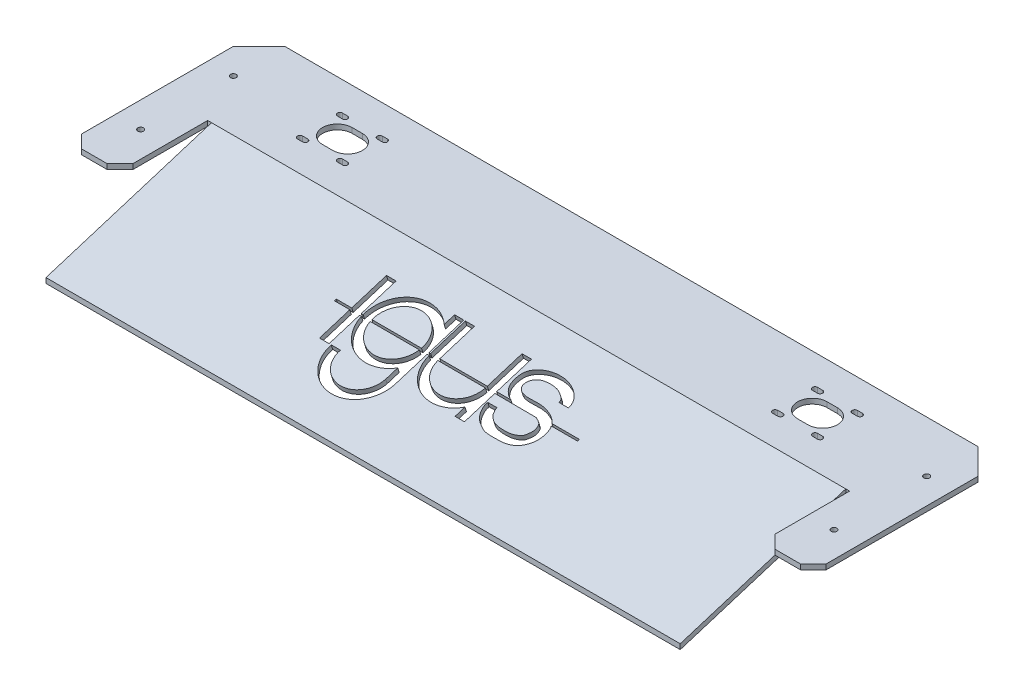
SolidWorks part; units mm, degrees
ref_plane "Front Plane" through (0, 0, 0) normal (0, 0, 1) x (1, 0, 0)
ref_plane "Top Plane" through (0, 0, 0) normal (0, 1, 0) x (1, 0, 0)
ref_plane "Right Plane" through (0, 0, 0) normal (1, 0, 0) x (0, 0, -1)
sketch "Sketch1" plane through (0, 0, 0) normal (0, 1, 0) x (1, 0, 0)
  line L0 (0, 0) -> (-290, 0) construction
  line L1 (-290, 0) -> (-290, 108.2843)
  line L2 (-290, 108.2843) -> (-250, 108.2843)
  line L3 (-250, 108.2843) -> (-250, 68.2843)
  line L4 (-250, 68.2843) -> (-221.7157, 40)
  line L5 (-221.7157, 40) -> (0, 40)
  line L6 (0, 40) -> (0, 0)
  line L7 (-290, 0) -> (0, 0)
  line L8 (-189, 0) -> (-181, 0) construction
  line L9 (-189, 11.5) -> (-181, 11.5)
  line L10 (-202.4998, 15.4998) -> (-198.4998, 15.4998) construction
  line L11 (-185, 0) -> (-220.6507, 35.6507) construction
  line L12 (-202.4998, 17.4998) -> (-198.4998, 17.4998)
  line L13 (-202.4998, 13.4998) -> (-198.4998, 13.4998)
  line L14 (-185, 11.5) -> (-185, 25.0205) construction
  line L15 (-167.5002, 15.4998) -> (-171.5002, 15.4998) construction
  line L16 (-167.5002, 17.4998) -> (-171.5002, 17.4998)
  line L17 (-167.5002, 13.4998) -> (-171.5002, 13.4998)
  arc A0 (-189, 11.5) -> (-200.5, 0) centre (-189, 0) ccw
  arc A1 (-169.5, 0) -> (-181, 11.5) centre (-181, 0) ccw
  arc A2 (-202.4998, 17.4998) -> (-202.4998, 13.4998) centre (-202.4998, 15.4998) ccw
  arc A3 (-198.4998, 13.4998) -> (-198.4998, 17.4998) centre (-198.4998, 15.4998) ccw
  arc A4 (-167.5002, 17.4998) -> (-167.5002, 13.4998) centre (-167.5002, 15.4998) cw
  arc A5 (-171.5002, 13.4998) -> (-171.5002, 17.4998) centre (-171.5002, 15.4998) cw
  point P10 (-185, 0)
  point P19 (-200.4998, 15.4998)
  point P28 (-169.5002, 15.4998)
  dimension "D9" = 11.5
  dimension "D11" = 2
  dimension "D1" = 290
  dimension "D2" = 40
  dimension "D3" = 40
  dimension "D4" = 40
  dimension "D5" = 40
  dimension "D6" = 135
  dimension "D7" = 185
  dimension "D8" = 4
  dimension "D10" = 21.92
  dimension "D12" = 4
extrude "Boss-Extrude1" add sketch "Sketch1" along normal blind 4 contours A1 L7 L6 L5 L4 L3 L2 L1 A0 L9
mirror "Mirror1" about plane through (0, 4, 0) normal (0, 0, -1) of "Boss-Extrude1"
mirror "Mirror5" about plane through (0, 4, 0) normal (1, 0, 0) of "Boss-Extrude1"
mirror "Mirror6" about plane through (0, 4, 0) normal (0, 0, 1) of "Mirror5"
sketch "Sketch2" plane through (0, 4, 0) normal (0, 1, 0) x (1, 0, 0)
  line L0 (-270, -36.0948) -> (-270, -72.1895)
  line L2 (-270, 36.0948) -> (-270, 0) construction
  line L3 (-270, 0) -> (-270, -36.0948) construction
  line L4 (-270, -72.1895) -> (-270, -108.2843)
  line L6 (-290, -108.2843) -> (-250, -108.2843) construction
  line L7 (-270, 36.0948) -> (-270, 72.1895)
  line L8 (-270, 72.1895) -> (-270, 108.2843)
  line L9 (-290, 108.2843) -> (-250, 108.2843) construction
  circle A0 centre (-270, 72.1895) radius 2.25
  circle A1 centre (-270, -72.1895) radius 2.25
  circle A2 centre (-270, 0) radius 2.25
  dimension "D1" = 4.5
extrude "Cut-Extrude1" cut sketch "Sketch2" against normal blind 44 contours L4 A1 L0 | L0 A1 L4 | A2 | L7 A0 L8 | L8 A0 L7
chamfer "Chamfer1" distance 10 angle 45 4 edges at (-250, 2, 108.2843) (-290, 2, 108.2843) (-290, 2, -108.2843) (-250, 2, -108.2843)
mirror "Mirror9" about plane through (0, 0, 0) normal (1, 0, 0) of "Cut-Extrude1"
chamfer "Chamfer2" distance 10 angle 45 4 edges at (290, 2, 108.2843) (250, 2, 108.2843) (250, 2, -108.2843) (290, 2, -108.2843)
sketch "Sketch3" plane through (0, 4, 0) normal (0, 1, 0) x (1, 0, 0)
  line L0 (-82.0648, 19.0507) -> (317.9352, 19.0507) construction
  line L1 (-21.8464, -9.8238) -> (-17.085, -9.8238)
  line L2 (-27.9324, 26.5851) -> (-22.9462, 26.5851)
  line L3 (-27.9324, 26.5851) -> (-27.9324, 7.69)
  line L4 (-27.9324, -9.8238) -> (-22.9462, -9.8238)
  line L5 (-22.9462, 26.5851) -> (-22.9462, 7.69)
  line L6 (7.4256, 20.9291) -> (7.4256, 26.5851)
  line L8 (48.1768, 1.992) -> (53.0651, 1.992)
  line L9 (12.1869, -10.8785) -> (12.1869, 26.5851)
  line L10 (12.1869, 26.5851) -> (7.4256, 26.5851)
  line L11 (7.4256, -10.8785) -> (7.4256, -4.32)
  line L12 (42.4602, 7.69) -> (42.4602, 26.5851)
  line L13 (42.4602, -9.8238) -> (47.3516, -9.8238)
  line L14 (42.4602, -9.8238) -> (42.4602, -4.4171)
  line L15 (42.4602, 26.5851) -> (47.3516, 26.5851)
  line L16 (47.3516, -9.8238) -> (47.3516, 6.6736)
  line L17 (70.9024, 16.7119) -> (75.9269, 16.7119)
  line L18 (17.7563, 26.5851) -> (13.034, 26.5851)
  line L19 (17.7563, 26.5851) -> (17.7563, 7.69)
  line L20 (17.7563, 7.69) -> (42.4602, 7.69)
  line L21 (13.034, 26.5851) -> (13.034, 7.69)
  line L22 (-27.9324, 6.6736) -> (-27.9324, -9.8238)
  line L23 (-35.9318, 7.69) -> (-27.9324, 7.69)
  line L24 (-35.9318, 7.69) -> (-35.9318, 6.6736)
  line L25 (-35.9318, 6.6736) -> (-27.9324, 6.6736)
  line L26 (82.484, 7.69) -> (82.484, 6.6736)
  line L27 (-22.9462, 7.69) -> (-22.0144, 7.69)
  line L28 (-22.9462, 6.6736) -> (-21.9488, 6.6736)
  line L29 (-22.9462, 6.6736) -> (-22.9462, -9.8238)
  line L30 (-17.4632, 7.69) -> (8.2752, 7.69)
  line L31 (-17.3742, 6.6736) -> (8.1862, 6.6736)
  line L32 (12.1869, 7.69) -> (13.034, 7.69)
  line L33 (12.1869, 6.6736) -> (13.2257, 6.6736)
  line L34 (17.7569, 6.6736) -> (42.4532, 6.6736)
  line L35 (76.0197, 7.69) -> (82.484, 7.69)
  line L36 (76.6898, 6.6736) -> (82.484, 6.6736)
  line L37 (47.3516, 7.69) -> (47.3516, 26.5851)
  line L38 (69.0253, 6.5779) -> (47.3516, 6.6736)
  line L39 (54.7056, 7.69) -> (47.3516, 7.69)
  circle A0 centre (-25.5805, 32.4181) radius 2.3986
  arc A1 (-17.3742, 6.6736) -> (8.1862, 6.6736) centre (-4.594, 8.3045) ccw
  arc A2 (7.4256, 20.9291) -> (-22.0144, 7.69) centre (-4.594, 8.3045) ccw
  arc A3 (-17.085, -9.8238) -> (7.4256, -10.8785) centre (-4.8297, -10.3511) ccw
  arc A4 (12.1869, -10.8785) -> (-21.8464, -9.8238) centre (-4.8297, -10.3511) cw
  arc A5 (17.7569, 6.6736) -> (42.4532, 6.6736) centre (30.105, 7.091) ccw
  arc A6 (13.2257, 6.6736) -> (42.4602, -4.4171) centre (30.105, 7.091) ccw
  arc A7 (-21.9488, 6.6736) -> (7.4256, -4.32) centre (-4.594, 8.3045) ccw
  arc A8 (8.2752, 7.69) -> (-17.4632, 7.69) centre (-4.594, 8.3045) ccw
  spline S0 degree 3 poles (75.9269, 16.7119) (76.1697, 20.3324) (70.9484, 25.553) (61.7695, 27.1891) (54.3456, 25.3692) (49.1183, 21.0552) (48.6509, 16.3068) (49.3938, 11.1111) (52.398, 8.5199) (54.7056, 7.69) knots 0 0 0 0 0.214336 0.39323 0.565847 0.67611 0.787927 0.84268 1 1 1 1
  spline S1 degree 3 poles (70.9024, 16.7119) (71.1665, 17.5271) (70.3325, 18.7995) (68.5625, 19.9226) (66.2905, 21.192) (63.4484, 21.6366) (60.1841, 21.5266) (57.2636, 21.0924) (54.8065, 19.4136) (53.435, 17.2465) (53.3745, 14.8515) (54.797, 13.1138) (58.5993, 11.576) (64.2118, 12.5728) (70.2856, 11.558) (74.0797, 9.743) (75.5817, 8.254) (76.0197, 7.69) knots 0 0 0 0 0.023974 0.0429 0.065707 0.104505 0.130316 0.168034 0.194386 0.220522 0.245719 0.2628 0.28726 0.369622 0.434467 0.476788 0.498808 0.498808 0.498808 0.498808
  spline S2 degree 3 poles (53.0651, 1.992) (52.8818, 1.0624) (53.4653, -0.024) (54.1041, -1.4919) (54.9804, -2.2675) (55.9906, -3.2538) (57.4527, -4.0034) (59.3948, -4.5243) (61.6145, -4.7083) (64.1331, -4.7695) (66.6176, -4.5389) (68.8285, -3.7825) (70.9655, -2.8167) (71.9855, -0.7891) (72.7896, 1.157) (72.6963, 3.0645) (72.0298, 5.4733) (69.9357, 6.0483) (69.0253, 6.5779) knots 0 0 0 0 0.081184 0.107905 0.143901 0.185104 0.235866 0.290216 0.366526 0.436729 0.518739 0.590002 0.64943 0.723575 0.786666 0.838093 0.894822 1 1 1 1
  spline S3 degree 3 poles (76.6898, 6.6736) (76.7767, 6.5153) (77.3461, 5.3791) (77.8424, 2.7751) (77.4957, -0.9697) (75.8419, -4.3239) (73.3769, -6.9875) (70.4757, -8.5808) (67.3839, -9.2832) (63.9164, -9.4499) (60.2497, -9.5065) (56.621, -9.1479) (53.7606, -7.5828) (51.0815, -5.941) (48.8083, -2.5373) (47.9106, 0.1666) (48.1768, 1.992) knots 0.51138 0.51138 0.51138 0.51138 0.516991 0.550898 0.592187 0.632311 0.665074 0.704087 0.733344 0.763284 0.81203 0.848329 0.874619 0.912981 0.944693 1 1 1 1
sketch "Sketch4" plane through (0, 4, 0) normal (0, 1, 0) x (1, 0, 0)
  line L0 (0, -40) -> (0, 40) construction
  line L1 (-221.7157, -40) -> (221.7157, -40) construction
  line L2 (-221.7157, 40) -> (221.7157, 40) construction
extrude "Cut-Extrude2" cut sketch "Sketch3" against normal blind 10 contours L0 L21 L32 L9 L33 A6 L14 L13 L16 L38 S2 L8 S3 L36 L26 L35 S1 S0 L39 L37 L12 L20 L19 A5 L34 | L0 L3 L23 L24 L25 L22 L4 L29 L28 A7 L11 A3 L1 A4 L9 A8 L30 A2 L27 L5 A1 L31 | L0 S1 L17 S0 | S0 L0 S1 | L12 L0 L37 L15 | L21 L0 L19 L18 | A2 L0 A8 L9 L10 L6 | L3 L0 L5 L2 | A0
sketch "Sketch5" plane through (0, 4, 0) normal (0, 1, 0) x (1, 0, 0)
  line L0 (-250, -68.2843) -> (-221.7157, -40)
  line L1 (-221.7157, -40) -> (-250, -40)
  line L2 (-250, -40) -> (-250, -68.2843)
  line L3 (221.7157, -40) -> (250, -68.2843)
  line L4 (250, -68.2843) -> (250, -40)
  line L5 (250, -40) -> (221.7157, -40)
extrude "Cut-Extrude3" cut sketch "Sketch5" against normal blind 10
sketch "Sketch6" plane through (0, 0, 0) normal (1, 0, 0) x (0, 0, -1)
  line L0 (-40, 4) -> (-168.938, -36)
  line L1 (-168.938, -36) -> (-168.938, -40)
  line L2 (-168.938, -40) -> (-40, 0)
  line L3 (-40, 0) -> (-40, 4)
  point P2 (0, 0)
  point P5 (0, 0)
  dimension "D1" = 135
  dimension "D2" = 40
extrude "Boss-Extrude2" add sketch "Sketch6" along normal mid plane 494
sketch "Sketch7" plane through (0, 14.9685, 4.6436) normal (0, 0.9551, 0.2963) x (1, 0, 0)
  line L0 (-74.9706, -119.5218) -> (-67.8286, -119.5218)
  line L1 (-84.0997, -64.9084) -> (-76.6204, -64.9084)
  line L2 (-84.0997, -64.9084) -> (-84.0997, -93.251)
  line L3 (-84.0997, -119.5218) -> (-76.6204, -119.5218)
  line L4 (-76.6204, -64.9084) -> (-76.6204, -93.251)
  line L5 (-31.0627, -73.3925) -> (-31.0627, -64.9084)
  line L6 (30.0641, -101.7981) -> (37.3966, -101.7981)
  line L7 (-23.9207, -121.1039) -> (-23.9207, -64.9084)
  line L8 (-23.9207, -64.9084) -> (-31.0627, -64.9084)
  line L9 (-31.0627, -121.1039) -> (-31.0627, -111.2661)
  line L10 (21.4893, -93.251) -> (21.4893, -64.9084)
  line L11 (21.4893, -119.5218) -> (28.8263, -119.5218)
  line L12 (21.4893, -119.5218) -> (21.4893, -111.4117)
  line L13 (21.4893, -64.9084) -> (28.8263, -64.9084)
  line L14 (28.8263, -119.5218) -> (28.8263, -94.7757)
  line L15 (64.1525, -79.7183) -> (71.6893, -79.7183)
  line L16 (-15.5666, -64.9084) -> (-22.65, -64.9084)
  line L17 (-15.5666, -64.9084) -> (-15.5666, -93.251)
  line L18 (-15.5666, -93.251) -> (21.4893, -93.251)
  line L19 (-22.65, -64.9084) -> (-22.65, -93.251)
  line L20 (-84.0997, -94.7757) -> (-84.0997, -119.5218)
  line L21 (-96.0988, -93.251) -> (-84.0997, -93.251)
  line L22 (-96.0988, -93.251) -> (-96.0988, -94.7757)
  line L23 (-96.0988, -94.7757) -> (-84.0997, -94.7757)
  line L24 (93.1423, -93.251) -> (93.1423, -94.7757)
  line L25 (-76.6204, -93.251) -> (-75.2227, -93.251)
  line L26 (-76.6204, -94.7757) -> (-75.1243, -94.7757)
  line L27 (-76.6204, -94.7757) -> (-76.6204, -119.5218)
  line L28 (-68.3958, -93.251) -> (-29.7883, -93.251)
  line L29 (-68.2624, -94.7757) -> (-29.9218, -94.7757)
  line L30 (-23.9207, -93.251) -> (-22.65, -93.251)
  line L31 (-23.9207, -94.7757) -> (-22.3625, -94.7757)
  line L32 (-15.5657, -94.7757) -> (21.4787, -94.7757)
  line L33 (71.8285, -93.251) -> (93.1423, -93.251)
  line L34 (72.8337, -94.7757) -> (93.1423, -94.7757)
  line L35 (28.8263, -93.251) -> (28.8263, -64.9084)
  line L36 (61.3369, -94.9193) -> (28.8263, -94.7757)
  line L37 (39.8573, -93.251) -> (28.8263, -93.251)
  line L38 (-96.0988, -94.7757) -> (-371.9782, -94.7757) construction
  line L40 (93.1423, -94.7757) -> (369.0218, -94.7757) construction
  circle A0 centre (-80.5717, -56.159) radius 3.5979
  arc A1 (-68.2624, -94.7757) -> (-29.9218, -94.7757) centre (-49.0921, -92.3293) ccw
  arc A2 (-31.0627, -73.3925) -> (-75.2227, -93.251) centre (-49.0921, -92.3293) ccw
  arc A3 (-67.8286, -119.5218) -> (-31.0627, -121.1039) centre (-49.4456, -120.3128) ccw
  arc A4 (-23.9207, -121.1039) -> (-74.9706, -119.5218) centre (-49.4456, -120.3128) cw
  arc A5 (-15.5657, -94.7757) -> (21.4787, -94.7757) centre (2.9565, -94.1497) ccw
  arc A6 (-22.3625, -94.7757) -> (21.4893, -111.4117) centre (2.9565, -94.1497) ccw
  arc A7 (-75.1243, -94.7757) -> (-31.0627, -111.2661) centre (-49.0921, -92.3293) ccw
  arc A8 (-29.7883, -93.251) -> (-68.3958, -93.251) centre (-49.0921, -92.3293) ccw
  spline S0 degree 3 poles (71.6893, -79.7183) (72.0536, -74.2875) (64.2215, -66.4567) (50.4532, -64.0025) (39.3174, -66.7324) (31.4763, -73.2033) (30.7753, -80.3259) (31.8896, -88.1195) (36.3959, -92.0062) (39.8573, -93.251) knots 0 0 0 0 0.214336 0.39323 0.565847 0.67611 0.787927 0.84268 1 1 1 1
  spline S1 degree 3 poles (64.1525, -79.7183) (64.5486, -78.4955) (63.2977, -76.5869) (60.6427, -74.9022) (57.2347, -72.9982) (52.9716, -72.3312) (48.075, -72.4963) (43.6944, -73.1475) (40.0087, -75.6657) (37.9514, -78.9163) (37.8607, -82.5089) (39.9945, -85.1154) (45.6979, -87.4221) (54.1166, -85.9268) (63.2273, -87.4491) (68.9185, -90.1717) (71.1716, -92.4052) (71.8285, -93.251) knots 0 0 0 0 0.023974 0.0429 0.065707 0.104505 0.130316 0.168034 0.194386 0.220522 0.245719 0.2628 0.28726 0.369622 0.434467 0.476788 0.498808 0.498808 0.498808 0.498808
  spline S2 degree 3 poles (37.3966, -101.7981) (37.1217, -103.1924) (37.9969, -104.8221) (38.9551, -107.0239) (40.2695, -108.1873) (41.7848, -109.6668) (43.978, -110.7913) (46.8911, -111.5726) (50.2207, -111.8486) (53.9986, -111.9403) (57.7254, -111.5945) (61.0418, -110.4599) (64.2473, -109.0111) (65.7772, -105.9697) (66.9834, -103.0506) (66.8435, -100.1894) (65.8437, -96.5761) (62.7025, -95.7137) (61.3369, -94.9193) knots 0 0 0 0 0.081184 0.107905 0.143901 0.185104 0.235866 0.290216 0.366526 0.436729 0.518739 0.590002 0.64943 0.723575 0.786666 0.838093 0.894822 1 1 1 1
  spline S3 degree 3 poles (72.8337, -94.7757) (72.964, -95.0131) (73.8181, -96.7175) (74.5625, -100.6235) (74.0425, -106.2407) (71.5619, -111.272) (67.8644, -115.2673) (63.5125, -117.6573) (58.8748, -118.7109) (53.6736, -118.961) (48.1735, -119.0459) (42.7305, -118.508) (38.4399, -116.1603) (34.4212, -113.6977) (31.0114, -108.592) (29.6648, -104.5362) (30.0641, -101.7981) knots 0.51138 0.51138 0.51138 0.51138 0.516991 0.550898 0.592187 0.632311 0.665074 0.704087 0.733344 0.763284 0.81203 0.848329 0.874619 0.912981 0.944693 1 1 1 1
extrude "Cut-Extrude4" cut sketch "Sketch7" against normal blind 494 contours L26 A7 L9 A3 L0 A4 L7 L8 L5 A2 L25 L4 L1 L2 L21 L22 L23 L20 L3 L27 A8 L28 A1 L29 | S3 L34 L24 L33 S1 L15 S0 L37 L35 L13 L10 L18 L17 L16 L19 L30 L7 L31 A6 L12 L11 L14 L36 S2 L6 A5 L32
sketch "Sketch8" plane through (0, 4, 0) normal (0, 1, 0) x (1, 0, 0)
  line L0 (-221.7157, 40) -> (221.7157, 40) construction
  line L1 (-117.7008, 40) -> (117.1851, 40)
  line L2 (-117.7008, 40) -> (-117.7008, -40)
  line L3 (-117.7008, -40) -> (117.1851, -40)
  line L4 (117.1851, 40) -> (117.1851, -40)
  line L5 (247, -40) -> (-247, -40) construction
extrude "Boss-Extrude3" add sketch "Sketch8" against normal up to surface (4 mm away) up to face at (-25.5805, 0, -30.0195)
sketch "Sketch9" plane through (0, 4, 0) normal (0, 1, 0) x (1, 0, 0)
  line L0 (221.7157, 40) -> (-221.7157, 40) construction
  line L1 (399.3947, 40) -> (-391.8377, 40)
  line L2 (399.3947, 40) -> (399.3947, 234.8199)
  line L3 (399.3947, 234.8199) -> (-391.8377, 234.8199)
  line L4 (-391.8377, 40) -> (-391.8377, 234.8199)
extrude "Cut-Extrude5" cut sketch "Sketch9" against normal blind 139
chamfer "Chamfer3" distance 20 angle 45 2 edges at (290, 2, -40) (-290, 2, -40)
